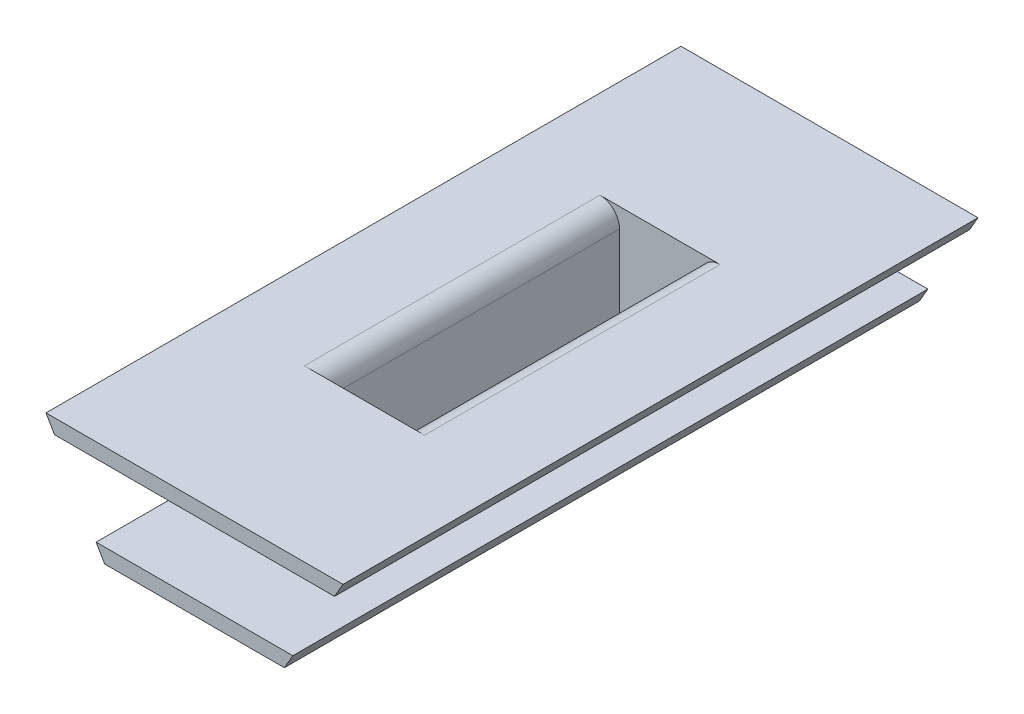
SolidWorks part; units mm, degrees
ref_plane "Front Plane" through (0, 0, 0) normal (0, 0, 1) x (1, 0, 0)
ref_plane "Top Plane" through (0, 0, 0) normal (0, 1, 0) x (1, 0, 0)
ref_plane "Right Plane" through (0, 0, 0) normal (1, 0, 0) x (0, 0, -1)
sketch "Casing" plane through (0, 0, 0) normal (0, 0, 1) x (1, 0, 0)
  line L0 (9.2, 0) -> (-9.2, 0)
  line L2 (0, 1.5) -> (0, 5.1962) construction
  line L4 (-9.2, 0) -> (-10.066, 1.5)
  line L5 (-15.2, 10.3923) -> (15.2, 10.3923)
  line L8 (9.2, 0) -> (10.066, 1.5)
  line L10 (-12.6019, 8.8923) -> (-5.15, 8.8923)
  line L12 (8.334, 1.5) -> (5.15, 1.5)
  line L14 (-14.334, 8.8923) -> (-5.15, 8.8923)
  line L16 (-10.066, 1.5) -> (-5.15, 1.5)
  line L17 (-14.334, 8.8923) -> (-15.2, 10.3923)
  line L18 (-9.2, 0) -> (-15.2, 10.3923) construction
  line L19 (14.334, 8.8923) -> (15.2, 10.3923)
  line L20 (9.2, 0) -> (15.2, 10.3923) construction
  line L21 (0, 5.1962) -> (-4.15, 5.1962) construction
  line L22 (-4.15, 8.8923) -> (-4.15, 1.5)
  line L23 (4.15, 8.8923) -> (4.15, 1.5)
  line L24 (-5.15, 8.8923) -> (-5.15, 1.5)
  line L25 (5.15, 8.8923) -> (5.15, 1.5)
  line L26 (-8.334, 1.5) -> (-12.6019, 8.8923) construction
  line L27 (8.334, 1.5) -> (12.6019, 8.8923) construction
  line L28 (4.15, 1.5) -> (-4.15, 1.5)
  line L29 (8.334, 1.5) -> (-8.334, 1.5) construction
  line L30 (5.15, 1.5) -> (10.066, 1.5)
  line L31 (5.15, 8.8923) -> (12.6019, 8.8923)
  line L32 (-12.6019, 8.8923) -> (12.6019, 8.8923) construction
  line L33 (5.15, 8.8923) -> (14.334, 8.8923)
  line L34 (-4.15, 1.5) -> (4.15, 1.5)
  line L35 (-5.15, 1.5) -> (-8.334, 1.5)
  line L36 (-4.15, 8.8923) -> (4.15, 8.8923)
  line L37 (-4.15, 8.8923) -> (4.15, 8.8923)
  line L38 (-12.6019, 8.8923) -> (-14.334, 8.8923)
  line L40 (12.6019, 8.8923) -> (14.334, 8.8923)
  line L41 (8.334, 1.5) -> (10.066, 1.5)
  point P8 (0, 10.3923)
  point P15 (0, 8.8923)
  point P18 (0, 1.5)
  point P22 (-4.15, 5.1962)
  dimension "D1" = 15.2
  dimension "D3" = 120
  dimension "D5" = 4.15
  dimension "D6" = 1
  dimension "D7" = 1
  dimension "D4" = 1.5
extrude "Boss-Extrude2" add sketch "Casing" along normal blind 65 contours L31 L33 L19 L5 L17 L14 L10 L24 L16 L4 L0 L8 L30 L12 L25 L22 L36 L23 L28 | L36 L22 L28 L23
sketch "Sketch10" plane through (0, 0, 65) normal (0, 0, 1) x (1, 0, 0)
  line L0 (-5.15, 1.5) -> (5.15, 1.5)
  line L1 (-5.15, 1.5) -> (-5.15, 8.8924)
  line L2 (5.15, 1.5) -> (5.15, 8.8924)
  line L3 (-5.15, 8.8924) -> (5.15, 8.8924)
extrude "Top_Cut" cut sketch "Sketch10" against normal blind 16.35
sketch "Sketch11" plane through (0, 0, 0) normal (0, 0, -1) x (-1, 0, 0)
  line L0 (-5.15, 1.5) -> (5.15, 1.5)
  line L1 (-5.15, 1.5) -> (-5.15, 8.9052)
  line L2 (5.15, 1.5) -> (5.15, 8.9052)
  line L3 (-5.15, 8.9052) -> (5.15, 8.9052)
extrude "Bot_Cut" cut sketch "Sketch11" against normal blind 16.35
sketch "Sketch13" plane through (0, 10.3923, 0) normal (0, 1, 0) x (1, 0, 0)
  line L0 (-5.15, -16.35) -> (5.15, -16.35)
  line L1 (-5.15, -16.35) -> (-5.15, -48.6057)
  line L2 (5.15, -16.35) -> (5.15, -48.6057)
  line L3 (-5.15, -48.6057) -> (5.15, -48.6057)
  line L4 (-4.15, -17.35) -> (4.15, -17.35)
  line L5 (4.15, -17.35) -> (4.15, -47.6057)
  line L6 (-4.15, -47.6057) -> (4.15, -47.6057)
  line L7 (-4.15, -17.35) -> (-4.15, -47.6057)
  dimension "D1" = 1
extrude "Cut-Extrude8" cut sketch "Sketch13" against normal through all contours L4 L5 L6 L7
fillet "Fillet1" radius 1 4 edges at (-5.15, 5.1962, 48.65) (5.15, 5.1962, 48.65) (-5.15, 5.1962, 16.35) (5.15, 5.1962, 16.35)
fillet "Fillet2" radius 2 2 edges at (4.15, 10.3923, 32.4778) (-4.15, 10.3923, 32.4778)
